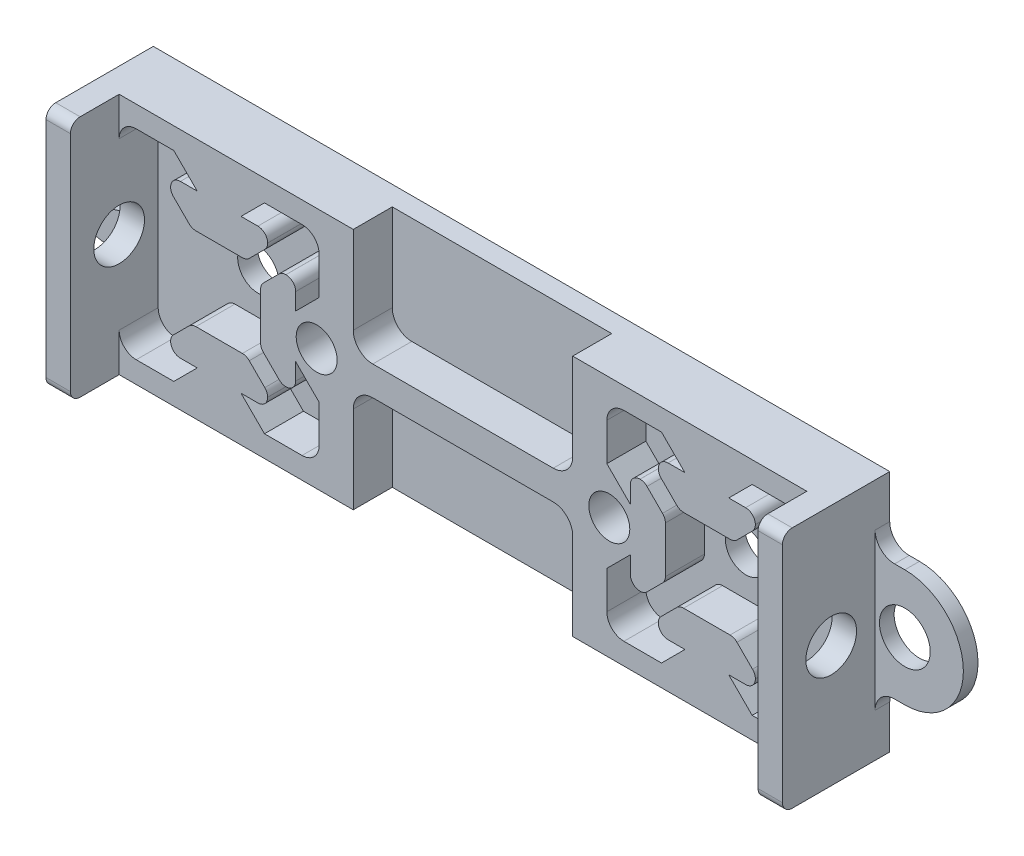
SolidWorks part; units mm, degrees
ref_plane "Front Plane" through (0, 0, 0) normal (0, 0, 1) x (1, 0, 0)
ref_plane "Top Plane" through (0, 0, 0) normal (0, 1, 0) x (1, 0, 0)
ref_plane "Right Plane" through (0, 0, 0) normal (1, 0, 0) x (0, 0, -1)
sketch "Sketch1" plane through (0, 0, 0) normal (0, 0, 1) x (1, 0, 0)
  line L0 (15.6876, 55.3211) -> (115.0437, 55.3211) construction
  line L1 (8.1, 5.225) -> (8.1, 2.85)
  line L2 (-8.5, 10) -> (-4.75, 10)
  line L3 (-10, 8.5) -> (-10, 4.75)
  line L4 (-8.5, -10) -> (-4.75, -10)
  line L5 (10, 8.5) -> (10, 4.75)
  line L6 (6.325, 5.225) -> (4, 2.9)
  line L7 (-8.1, -2.85) -> (-8.1, -5.225)
  line L8 (-2.9, 4) -> (2.9, 4)
  line L9 (-4, 2.9) -> (-4, -2.9)
  line L10 (-2.9, -4) -> (2.9, -4)
  line L11 (4, 2.9) -> (4, -2.9)
  line L12 (2.85, -8.1) -> (5.225, -8.1)
  line L13 (-5.225, -8.1) -> (-2.85, -8.1)
  line L14 (5.225, 6.325) -> (2.9, 4)
  line L15 (-6.4286, 4.975) -> (-4.25, 2.7964)
  line L16 (-4.25, 2.7964) -> (-4.25, -2.7964)
  line L17 (-10, 4.75) -> (-8.1, 2.85)
  line L18 (-4.25, -2.7964) -> (-6.4286, -4.975)
  line L19 (-7.85, -4.975) -> (-6.4286, -4.975)
  line L20 (4.75, -10) -> (8.5, -10)
  line L21 (-7.85, -2.2464) -> (-7.85, -4.975)
  line L22 (-10, -4.75) -> (-10, -8.5)
  line L23 (10, -4.75) -> (10, -8.5)
  line L24 (-10, -4.75) -> (-8.1, -2.85)
  line L25 (-4.75, -10) -> (-2.85, -8.1)
  line L26 (4.75, -10) -> (2.85, -8.1)
  line L27 (10, -4.75) -> (8.1, -2.85)
  line L28 (10, 4.75) -> (8.1, 2.85)
  line L29 (-4.75, 10) -> (-2.85, 8.1)
  line L30 (4.75, 10) -> (2.85, 8.1)
  line L31 (8.1, -2.85) -> (8.1, -5.225)
  line L32 (6.325, -5.225) -> (8.1, -5.225)
  line L33 (5.225, -6.325) -> (5.225, -8.1)
  line L34 (4.75, 10) -> (8.5, 10)
  line L35 (2.85, 8.1) -> (5.225, 8.1)
  line L36 (10, -10) -> (10.975, -10.975) construction
  line L37 (-5.225, 8.1) -> (-2.85, 8.1)
  line L38 (-8.1, -5.225) -> (-6.325, -5.225)
  line L39 (-5.225, 6.325) -> (-2.9, 4)
  line L40 (-8.1, 5.225) -> (-8.1, 2.85)
  line L41 (-5.225, -6.325) -> (-5.225, -8.1)
  line L42 (-6.325, 5.225) -> (-4, 2.9)
  line L43 (-10.25, -4.6464) -> (-7.85, -2.2464)
  line L44 (-10.25, -4.6464) -> (-10.25, -8.5)
  line L45 (-8.5, -10.25) -> (-4.6464, -10.25)
  line L46 (-8.1, 5.225) -> (-6.325, 5.225)
  line L47 (-5.225, 8.1) -> (-5.225, 6.325)
  line L48 (-4.6464, -10.25) -> (-2.2464, -7.85)
  line L49 (-4.975, -7.85) -> (-2.2464, -7.85)
  line L50 (-4.975, -6.4286) -> (-4.975, -7.85)
  line L51 (-2.7964, -4.25) -> (-4.975, -6.4286)
  line L52 (8.1, 5.225) -> (6.325, 5.225)
  line L53 (5.225, 8.1) -> (5.225, 6.325)
  line L54 (-2.7964, -4.25) -> (2.7964, -4.25)
  line L55 (2.7964, -4.25) -> (4.975, -6.4286)
  line L56 (4.975, -6.4286) -> (4.975, -7.85)
  line L57 (2.2464, -7.85) -> (4.975, -7.85)
  line L58 (4.6464, -10.25) -> (2.2464, -7.85)
  line L59 (4.6464, -10.25) -> (8.5, -10.25)
  line L60 (10.25, -4.6464) -> (10.25, -8.5)
  line L61 (10.25, -4.6464) -> (7.85, -2.2464)
  line L62 (7.85, -2.2464) -> (7.85, -4.975)
  line L63 (4, -2.9) -> (6.325, -5.225)
  line L64 (6.4286, -4.975) -> (7.85, -4.975)
  line L65 (4.25, -2.7964) -> (6.4286, -4.975)
  line L66 (2.9, -4) -> (5.225, -6.325)
  line L67 (-2.9, -4) -> (-5.225, -6.325)
  line L68 (4.25, 2.7964) -> (4.25, -2.7964)
  line L69 (6.4286, 4.975) -> (4.25, 2.7964)
  line L70 (-4, -2.9) -> (-6.325, -5.225)
  line L71 (7.85, 4.975) -> (6.4286, 4.975)
  line L72 (7.85, 4.975) -> (7.85, 2.2464)
  line L73 (10.25, 4.6464) -> (7.85, 2.2464)
  line L74 (10.25, 8.5) -> (10.25, 4.6464)
  line L75 (4.6464, 10.25) -> (8.5, 10.25)
  line L76 (4.6464, 10.25) -> (2.2464, 7.85)
  line L77 (2.2464, 7.85) -> (4.975, 7.85)
  line L78 (4.975, 7.85) -> (4.975, 6.4286)
  line L79 (4.975, 6.4286) -> (2.7964, 4.25)
  line L80 (-2.7964, 4.25) -> (2.7964, 4.25)
  line L81 (-4.975, 6.4286) -> (-2.7964, 4.25)
  line L82 (-4.975, 7.85) -> (-4.975, 6.4286)
  line L83 (-4.975, 7.85) -> (-2.2464, 7.85)
  line L84 (-4.6464, 10.25) -> (-2.2464, 7.85)
  line L85 (-8.5, 10.25) -> (-4.6464, 10.25)
  line L86 (-10.25, 8.5) -> (-10.25, 4.6464)
  line L87 (-10.25, 4.6464) -> (-7.85, 2.2464)
  line L88 (-7.85, 4.975) -> (-7.85, 2.2464)
  line L89 (-7.85, 4.975) -> (-6.4286, 4.975)
  line L90 (0, 0) -> (74.0125, 0.5542) construction
  line L91 (25, 17.7637) -> (25, -17.7695) construction
  line L92 (40, -10) -> (39.025, -10.975) construction
  line L93 (57.85, 4.975) -> (56.4286, 4.975)
  line L94 (57.85, 4.975) -> (57.85, 2.2464)
  line L95 (60.25, 4.6464) -> (57.85, 2.2464)
  line L96 (60.25, 8.5) -> (60.25, 4.6464)
  line L97 (54.6464, 10.25) -> (52.2464, 7.85)
  line L98 (54.975, 7.85) -> (52.2464, 7.85)
  line L99 (54.975, 7.85) -> (54.975, 6.4286)
  line L100 (54.975, 6.4286) -> (52.7964, 4.25)
  line L101 (52.7964, 4.25) -> (47.2036, 4.25)
  line L102 (45.025, 6.4286) -> (47.2036, 4.25)
  line L103 (45.025, 7.85) -> (45.025, 6.4286)
  line L104 (47.7536, 7.85) -> (45.025, 7.85)
  line L105 (45.3536, 10.25) -> (47.7536, 7.85)
  line L106 (45.3536, 10.25) -> (41.5, 10.25)
  line L107 (39.75, 8.5) -> (39.75, 4.6464)
  line L108 (39.75, 4.6464) -> (42.15, 2.2464)
  line L109 (42.15, 4.975) -> (42.15, 2.2464)
  line L110 (42.15, 4.975) -> (43.5714, 4.975)
  line L111 (54, -2.9) -> (56.325, -5.225)
  line L112 (43.5714, 4.975) -> (45.75, 2.7964)
  line L113 (45.75, 2.7964) -> (45.75, -2.7964)
  line L114 (52.9, -4) -> (55.225, -6.325)
  line L115 (47.1, -4) -> (44.775, -6.325)
  line L116 (45.75, -2.7964) -> (43.5714, -4.975)
  line L117 (43.5714, -4.975) -> (42.15, -4.975)
  line L118 (46, -2.9) -> (43.675, -5.225)
  line L119 (42.15, -2.2464) -> (42.15, -4.975)
  line L120 (39.75, -4.6464) -> (42.15, -2.2464)
  line L121 (39.75, -4.6464) -> (39.75, -8.5)
  line L122 (45.3536, -10.25) -> (41.5, -10.25)
  line L123 (45.3536, -10.25) -> (47.7536, -7.85)
  line L124 (47.7536, -7.85) -> (45.025, -7.85)
  line L125 (45.025, -6.4286) -> (45.025, -7.85)
  line L126 (47.2036, -4.25) -> (45.025, -6.4286)
  line L127 (52.7964, -4.25) -> (47.2036, -4.25)
  line L128 (44.775, 8.1) -> (44.775, 6.325)
  line L129 (41.9, 5.225) -> (43.675, 5.225)
  line L130 (52.7964, -4.25) -> (54.975, -6.4286)
  line L131 (54.975, -6.4286) -> (54.975, -7.85)
  line L132 (54.975, -7.85) -> (52.2464, -7.85)
  line L133 (54.6464, -10.25) -> (52.2464, -7.85)
  line L134 (55.225, 8.1) -> (55.225, 6.325)
  line L135 (58.1, 5.225) -> (56.325, 5.225)
  line L136 (58.5, -10.25) -> (54.6464, -10.25)
  line L137 (60.25, -4.6464) -> (60.25, -8.5)
  line L138 (60.25, -4.6464) -> (57.85, -2.2464)
  line L139 (56.325, 5.225) -> (54, 2.9)
  line L140 (55.225, -6.325) -> (55.225, -8.1)
  line L141 (58.1, 5.225) -> (58.1, 2.85)
  line L142 (55.225, 6.325) -> (52.9, 4)
  line L143 (58.1, -5.225) -> (56.325, -5.225)
  line L144 (55.225, 8.1) -> (52.85, 8.1)
  line L145 (47.15, 8.1) -> (44.775, 8.1)
  line L146 (45.25, 10) -> (41.5, 10)
  line L147 (44.775, -6.325) -> (44.775, -8.1)
  line L148 (43.675, -5.225) -> (41.9, -5.225)
  line L149 (41.9, -2.85) -> (41.9, -5.225)
  line L150 (45.25, 10) -> (47.15, 8.1)
  line L151 (54.75, 10) -> (52.85, 8.1)
  line L152 (40, 4.75) -> (41.9, 2.85)
  line L153 (40, -4.75) -> (41.9, -2.85)
  line L154 (45.25, -10) -> (47.15, -8.1)
  line L155 (54.75, -10) -> (52.85, -8.1)
  line L156 (60, -4.75) -> (58.1, -2.85)
  line L157 (40, -4.75) -> (40, -8.5)
  line L158 (60, -4.75) -> (60, -8.5)
  line L159 (57.85, -2.2464) -> (57.85, -4.975)
  line L160 (45.25, -10) -> (41.5, -10)
  line L161 (57.85, -4.975) -> (56.4286, -4.975)
  line L162 (54.25, -2.7964) -> (56.4286, -4.975)
  line L163 (60, 4.75) -> (58.1, 2.85)
  line L164 (54.25, 2.7964) -> (54.25, -2.7964)
  line L165 (56.4286, 4.975) -> (54.25, 2.7964)
  line L166 (44.775, 6.325) -> (47.1, 4)
  line L167 (55.225, -8.1) -> (52.85, -8.1)
  line L168 (47.15, -8.1) -> (44.775, -8.1)
  line L169 (46, 2.9) -> (46, -2.9)
  line L170 (52.9, -4) -> (47.1, -4)
  line L171 (54, 2.9) -> (54, -2.9)
  line L172 (52.9, 4) -> (47.1, 4)
  line L173 (58.1, -2.85) -> (58.1, -5.225)
  line L174 (43.675, 5.225) -> (46, 2.9)
  line L175 (40, 8.5) -> (40, 4.75)
  line L176 (58.5, -10) -> (54.75, -10)
  line L177 (60, 8.5) -> (60, 4.75)
  line L178 (58.5, 10) -> (54.75, 10)
  line L179 (41.9, 5.225) -> (41.9, 2.85)
  line L180 (58.5, 10.25) -> (54.6464, 10.25)
  line L182 (-12.75, -12.4529) -> (62.75, -12.4529)
  line L183 (-12.75, -12.4529) -> (-12.75, 12.4471)
  line L184 (-12.75, 12.4471) -> (62.75, 12.4471)
  line L185 (62.75, -12.4529) -> (62.75, 12.4471)
  line L186 (-12.75, -12.4529) -> (62.75, 12.4471) construction
  line L187 (-12.75, 12.4471) -> (62.75, -12.4529) construction
  arc A0 (-8.5, -10) -> (-10, -8.5) centre (-8.5, -8.5) cw
  arc A1 (8.5, -10) -> (10, -8.5) centre (8.5, -8.5) ccw
  arc A2 (10, 8.5) -> (8.5, 10) centre (8.5, 8.5) ccw
  arc A3 (-8.5, 10) -> (-10, 8.5) centre (-8.5, 8.5) ccw
  circle A4 centre (0, 0) radius 2.125
  arc A5 (-8.5, -10.25) -> (-10.25, -8.5) centre (-8.5, -8.5) cw
  arc A6 (8.5, -10.25) -> (10.25, -8.5) centre (8.5, -8.5) ccw
  arc A7 (10.25, 8.5) -> (8.5, 10.25) centre (8.5, 8.5) ccw
  arc A8 (-8.5, 10.25) -> (-10.25, 8.5) centre (-8.5, 8.5) ccw
  arc A9 (58.5, 10.25) -> (60.25, 8.5) centre (58.5, 8.5) cw
  arc A10 (39.75, 8.5) -> (41.5, 10.25) centre (41.5, 8.5) cw
  arc A11 (41.5, -10.25) -> (39.75, -8.5) centre (41.5, -8.5) cw
  arc A12 (58.5, -10.25) -> (60.25, -8.5) centre (58.5, -8.5) ccw
  circle A13 centre (50, 0) radius 2.125
  arc A14 (58.5, 10) -> (60, 8.5) centre (58.5, 8.5) cw
  arc A15 (40, 8.5) -> (41.5, 10) centre (41.5, 8.5) cw
  arc A16 (41.5, -10) -> (40, -8.5) centre (41.5, -8.5) cw
  arc A17 (58.5, -10) -> (60, -8.5) centre (58.5, -8.5) ccw
  point P2 (0, 0)
  point P8 (0, 0)
  point P14 (-10, -10)
  point P20 (0, 0)
  point P49 (10, 10)
  point P52 (-10, 10)
  point P120 (-10, -6.625)
  point P124 (25, -0.0029)
  point P189 (60, 10)
  point P214 (40, 10)
  point P231 (60, -10)
  dimension "D3" = 1.5
  dimension "D4" = 4.25
  dimension "D1" = 20
  dimension "D2" = 20
  dimension "D5" = 0.25
  dimension "D6" = 70
  dimension "D7" = 2.1971
  dimension "D8" = 75.5
  dimension "D9" = 24.9
  dimension "D13" = 5.25
  dimension "D14" = 5.25
  dimension "D15" = 90
  dimension "D16" = 5.25
  dimension "D17" = 5.25
  dimension "D18" = 5.25
  dimension "D19" = 5.25
  dimension "D20" = 5.25
  dimension "D21" = 5.25
  dimension "D22" = 90
  dimension "D23" = 90
  dimension "D24" = 90
  dimension "D25" = 2.85
  dimension "D26" = 2.85
  dimension "D27" = 2.85
  dimension "D28" = 2.85
extrude "Boss-Extrude1" add sketch "Sketch1" along normal blind 4 contours L182 L185 L184 L183 A12 L136 L133 L132 L131 L130 L127 L126 L125 L124 L123 L122 A11 L121 L120 L119 L117 L116 L113 L112 L110 L109 L108 L107 A10 L106 L105 L104 L103 L102 L101 L100 L99 L98 L97 L180 A9 L96 L95 L94 L93 L165 L164 L162 L161 L159
sketch "Sketch2" plane through (0, 0, 0) normal (0, 0, -1) x (-1, 0, 0)
  line L1 (-62.75, 12.4471) -> (12.75, 12.4471)
  line L2 (-62.75, 12.4471) -> (-62.75, -12.4529)
  line L3 (-62.75, -12.4529) -> (12.75, -12.4529)
  line L4 (12.75, 12.4471) -> (12.75, -12.4529)
extrude "Boss-Extrude2" add sketch "Sketch2" along normal blind 2
sketch "Sketch3" plane through (0, 0, 4) normal (0, 0, 1) x (1, 0, 0)
  line L0 (25, 12.4471) -> (25, -12.4529) construction
  line L1 (-12.75, 12.4471) -> (62.75, 12.4471) construction
  line L2 (-12.75, -12.4529) -> (62.75, -12.4529) construction
  line L4 (13.75, -12.4529) -> (36.25, -12.4529)
  line L5 (13.75, -12.4529) -> (13.75, 12.4471)
  line L6 (13.75, 12.4471) -> (36.25, 12.4471)
  line L7 (36.25, -12.4529) -> (36.25, 12.4471)
  line L8 (13.75, -12.4529) -> (36.25, 12.4471) construction
  line L9 (13.75, 12.4471) -> (36.25, -12.4529) construction
  point P6 (25, -0.0029)
  dimension "D1" = 22.5
extrude "Cut-Extrude1" cut sketch "Sketch3" against normal blind 4
fillet "Fillet1" radius 1 48 edges at (-4.25, -2.7964, 2) (-6.4286, -4.975, 2) (-7.85, -4.975, 2) (-4.975, -7.85, 2) (-4.975, -6.4286, 2) (-2.7964, -4.25, 2) (2.7964, -4.25, 2) (4.975, -6.4286, 2) (4.975, -7.85, 2) (7.85, -4.975, 2) (6.4286, -4.975, 2) (4.25, -2.7964, 2) (4.25, 2.7964, 2) (6.4286, 4.975, 2) (7.85, 4.975, 2) (4.975, 7.85, 2) (4.975, 6.4286, 2) (2.7964, 4.25, 2) (-4.25, 2.7964, 2) (-2.7964, 4.25, 2) (-6.4286, 4.975, 2) (-7.85, 4.975, 2) (-4.975, 6.4286, 2) (-4.975, 7.85, 2) (45.025, -7.85, 2) (42.15, -4.975, 2) (43.5714, -4.975, 2) (45.025, -6.4286, 2) (47.2036, -4.25, 2) (45.75, -2.7964, 2) (52.7964, -4.25, 2) (54.975, -6.4286, 2) (54.975, -7.85, 2) (54.25, -2.7964, 2) (56.4286, -4.975, 2) (57.85, -4.975, 2) (54.25, 2.7964, 2) (56.4286, 4.975, 2) (57.85, 4.975, 2) (45.75, 2.7964, 2) (43.5714, 4.975, 2) (42.15, 4.975, 2) (54.975, 6.4286, 2) (54.975, 7.85, 2) (52.7964, 4.25, 2) (47.2036, 4.25, 2) (45.025, 6.4286, 2) (45.025, 7.85, 2)
sketch "Sketch4" plane through (0, 0, 0) normal (0, 0, 1) x (1, 0, 0)
  line L0 (25, 12.4471) -> (25, -12.4529) construction
  line L1 (36.25, 12.4471) -> (13.75, 12.4471) construction
  line L2 (13.75, -12.4529) -> (36.25, -12.4529) construction
  circle A0 centre (0, 0) radius 2.1
  circle A1 centre (50, 0) radius 2.1
  dimension "D1" = 4.2
extrude "Cut-Extrude2" cut sketch "Sketch4" against normal through all
sketch "Sketch5" plane through (0, 0, 4) normal (0, 0, 1) x (1, 0, 0)
  line L0 (-12.75, -12.4529) -> (13.75, -12.4529) construction
  line L1 (-12.75, 12.4471) -> (-10.25, 12.4471)
  line L2 (-12.75, 12.4471) -> (-12.75, -12.4529)
  line L3 (-12.75, -12.4529) -> (-10.25, -12.4529)
  line L4 (-10.25, 12.4471) -> (-10.25, -12.4529)
  line L5 (36.25, -12.4529) -> (62.75, -12.4529) construction
  line L6 (62.75, 12.4471) -> (60.25, 12.4471)
  line L7 (62.75, 12.4471) -> (62.75, -12.4529)
  line L8 (62.75, -12.4529) -> (60.25, -12.4529)
  line L9 (60.25, 12.4471) -> (60.25, -12.4529)
  dimension "D1" = 2.5
  dimension "D2" = 2.5
extrude "Boss-Extrude3" add sketch "Sketch5" along normal blind 5
sketch "Sketch7" plane through (0, 0, 4) normal (0, 0, 1) x (1, 0, 0)
  line L5 (-7.85, 2.2464) -> (-10.25, 4.6464)
  line L6 (-7.85, 2.2464) -> (-10.25, 4.6464)
  line L7 (-10.25, 4.6464) -> (-10.25, -4.6464)
  line L8 (-10.25, 4.6464) -> (-10.25, -4.6464)
  line L9 (-10.25, -4.6464) -> (-7.85, -2.2464)
  line L10 (-10.25, -4.6464) -> (-7.85, -2.2464)
  line L11 (-7.85, -2.2464) -> (-7.85, -3.975)
  line L18 (-7.85, -2.2464) -> (-7.85, -3.975)
  line L19 (-6.85, -4.975) -> (-6.8428, -4.975)
  line L20 (-6.85, -4.975) -> (-6.8428, -4.975)
  line L21 (-6.1357, -4.6821) -> (-4.5429, -3.0893)
  line L22 (-6.1357, -4.6821) -> (-4.5429, -3.0893)
  line L23 (-4.25, -2.3822) -> (-4.25, 2.3822)
  line L24 (-4.25, -2.3822) -> (-4.25, 2.3822)
  line L25 (-4.5429, 3.0893) -> (-6.1357, 4.6821)
  line L26 (-4.5429, 3.0893) -> (-6.1357, 4.6821)
  line L27 (-6.8428, 4.975) -> (-6.85, 4.975)
  line L28 (-6.8428, 4.975) -> (-6.85, 4.975)
  line L29 (-7.85, 3.975) -> (-7.85, 2.2464)
  line L30 (-7.85, 3.975) -> (-7.85, 2.2464)
  line L41 (57.85, -2.2464) -> (60.25, -4.6464)
  line L42 (60.25, -4.6464) -> (60.25, 4.6464)
  line L43 (60.25, 4.6464) -> (57.85, 2.2464)
  line L44 (57.85, 2.2464) -> (57.85, 3.975)
  line L45 (56.85, 4.975) -> (56.8428, 4.975)
  line L46 (56.1357, 4.6821) -> (54.5429, 3.0893)
  line L47 (54.25, 2.3822) -> (54.25, -2.3822)
  line L48 (54.5429, -3.0893) -> (56.1357, -4.6821)
  line L49 (56.8428, -4.975) -> (56.85, -4.975)
  line L50 (57.85, -3.975) -> (57.85, -2.2464)
  line L51 (57.85, -2.2464) -> (60.25, -4.6464)
  line L52 (60.25, -4.6464) -> (60.25, 4.6464)
  line L53 (60.25, 4.6464) -> (57.85, 2.2464)
  line L54 (57.85, 2.2464) -> (57.85, 3.975)
  line L55 (56.85, 4.975) -> (56.8428, 4.975)
  line L56 (56.1357, 4.6821) -> (54.5429, 3.0893)
  line L57 (54.25, 2.3822) -> (54.25, -2.3822)
  line L58 (54.5429, -3.0893) -> (56.1357, -4.6821)
  line L59 (56.8428, -4.975) -> (56.85, -4.975)
  line L60 (57.85, -3.975) -> (57.85, -2.2464)
  arc A6 (-7.85, -3.975) -> (-6.85, -4.975) centre (-6.85, -3.975) ccw
  arc A7 (-7.85, -3.975) -> (-6.85, -4.975) centre (-6.85, -3.975) ccw
  arc A8 (-6.8428, -4.975) -> (-6.1357, -4.6821) centre (-6.8428, -3.975) ccw
  arc A9 (-6.8428, -4.975) -> (-6.1357, -4.6821) centre (-6.8428, -3.975) ccw
  arc A10 (-4.5429, -3.0893) -> (-4.25, -2.3822) centre (-5.25, -2.3822) ccw
  arc A11 (-4.5429, -3.0893) -> (-4.25, -2.3822) centre (-5.25, -2.3822) ccw
  arc A12 (-4.25, 2.3822) -> (-4.5429, 3.0893) centre (-5.25, 2.3822) ccw
  arc A13 (-4.25, 2.3822) -> (-4.5429, 3.0893) centre (-5.25, 2.3822) ccw
  arc A14 (-6.1357, 4.6821) -> (-6.8428, 4.975) centre (-6.8428, 3.975) ccw
  arc A15 (-6.1357, 4.6821) -> (-6.8428, 4.975) centre (-6.8428, 3.975) ccw
  arc A16 (-6.85, 4.975) -> (-7.85, 3.975) centre (-6.85, 3.975) ccw
  arc A17 (-6.85, 4.975) -> (-7.85, 3.975) centre (-6.85, 3.975) ccw
  arc A24 (57.85, 3.975) -> (56.85, 4.975) centre (56.85, 3.975) ccw
  arc A25 (56.8428, 4.975) -> (56.1357, 4.6821) centre (56.8428, 3.975) ccw
  arc A26 (54.5429, 3.0893) -> (54.25, 2.3822) centre (55.25, 2.3822) ccw
  arc A27 (54.25, -2.3822) -> (54.5429, -3.0893) centre (55.25, -2.3822) ccw
  arc A28 (56.1357, -4.6821) -> (56.8428, -4.975) centre (56.8428, -3.975) ccw
  arc A29 (56.85, -4.975) -> (57.85, -3.975) centre (56.85, -3.975) ccw
  arc A30 (57.85, 3.975) -> (56.85, 4.975) centre (56.85, 3.975) ccw
  arc A31 (56.8428, 4.975) -> (56.1357, 4.6821) centre (56.8428, 3.975) ccw
  arc A32 (54.5429, 3.0893) -> (54.25, 2.3822) centre (55.25, 2.3822) ccw
  arc A33 (54.25, -2.3822) -> (54.5429, -3.0893) centre (55.25, -2.3822) ccw
  arc A34 (56.1357, -4.6821) -> (56.8428, -4.975) centre (56.8428, -3.975) ccw
  arc A35 (56.85, -4.975) -> (57.85, -3.975) centre (56.85, -3.975) ccw
  dimension "D2" = 0
  dimension "D1" = 0
sketch "Sketch8" plane through (62.75, 0, 0) normal (1, 0, 0) x (0, 0, -1)
  line L0 (-9, -0.0029) -> (2, -0.0029) construction
  line L1 (-9, -12.4529) -> (-9, 12.4471) construction
  line L2 (2, 12.4471) -> (2, -12.4529) construction
  circle A0 centre (-4, -0.0029) radius 2.6
  dimension "D1" = 5
  dimension "D2" = 5.2
extrude "Cut-Extrude4" cut sketch "Sketch8" against normal blind 2.5
sketch "Sketch9" plane through (-12.75, 0, 0) normal (-1, 0, 0) x (0, 0, 1)
  line L0 (9, 0) -> (-2, 0) construction
  line L1 (9, 12.4471) -> (9, -12.4529) construction
  line L2 (-2, -12.4529) -> (-2, 12.4471) construction
  circle A0 centre (4, 0) radius 2.6
  dimension "D1" = 5.2
  dimension "D2" = 5
extrude "Cut-Extrude5" cut sketch "Sketch9" against normal blind 2.5
sketch "Sketch10" plane through (0, 0, -2) normal (0, 0, -1) x (-1, 0, 0)
  line L0 (-25, -12.4529) -> (-25, 12.4471) construction
  line L1 (-62.75, -12.4529) -> (12.75, -12.4529) construction
  line L2 (12.75, 12.4471) -> (-62.75, 12.4471) construction
  line L3 (0, 0) -> (-50, 0) construction
  circle A0 centre (-10, 0) radius 2.1
  circle A1 centre (-40, 0) radius 2.1
  dimension "D1" = 30
  dimension "D2" = 4.2
extrude "Cut-Extrude6" cut sketch "Sketch10" against normal through all
extrude "Cut-Extrude7" cut sketch "Sketch7" against normal blind 4
sketch "Sketch11" plane through (0, 0, 0) normal (0, 0, 1) x (1, 0, 0)
  line L0 (36.25, -0.0029) -> (13.75, -0.0029) construction
  line L1 (36.25, -12.4529) -> (36.25, 12.4471) construction
  line L2 (13.75, 12.4471) -> (13.75, -12.4529) construction
  line L4 (36.25, 1.4971) -> (13.75, 1.4971)
  line L5 (36.25, 1.4971) -> (36.25, -1.5029)
  line L6 (36.25, -1.5029) -> (13.75, -1.5029)
  line L7 (13.75, 1.4971) -> (13.75, -1.5029)
  line L8 (36.25, 1.4971) -> (13.75, -1.5029) construction
  line L9 (36.25, -1.5029) -> (13.75, 1.4971) construction
  point P6 (25, -0.0029)
  dimension "D1" = 3
extrude "Boss-Extrude4" add sketch "Sketch11" along normal up to surface (4 mm away) up to face at (42.1, 0, 4)
fillet "Fillet2" radius 2 4 edges at (13.75, -1.5029, 2) (13.75, 1.4971, 2) (36.25, 1.4971, 2) (36.25, -1.5029, 2)
fillet "Fillet3" radius 1 4 edges at (-11.5, 12.4471, 9) (-11.5, -12.4529, 9) (61.5, 12.4471, 9) (61.5, -12.4529, 9)
sketch "Sketch12" plane through (0, 0, -2) normal (0, 0, -1) x (-1, 0, 0)
  line L0 (25.9887, 0) -> (-76.4862, 0) construction
  line L1 (-25, -12.4529) -> (-25, 12.4471) construction
  line L2 (-62.75, -12.4529) -> (12.75, -12.4529) construction
  line L3 (12.75, 12.4471) -> (-62.75, 12.4471) construction
  line L4 (15.8, -6) -> (12.75, -6)
  line L5 (12.75, -12.4529) -> (12.75, 12.4471) construction
  line L6 (12.75, -6) -> (12.75, 6)
  line L7 (12.75, 6) -> (15.8, 6)
  line L8 (-62.75, -6) -> (-62.75, 6)
  line L9 (-65.8, -6) -> (-62.75, -6)
  line L10 (-62.75, 6) -> (-65.8, 6)
  circle A0 centre (15.8, 0) radius 2.6
  circle A1 centre (15.8, 0) radius 6
  circle A2 centre (-65.8, 0) radius 2.6
  circle A3 centre (-65.8, 0) radius 6
  line M8 (-62.75, 12.4471) -> (-62.75, -12.4529)
  line M10 (12.75, -12.4529) -> (12.75, 12.4471)
  dimension "D1" = 5.2
  dimension "D2" = 81.6
  dimension "D3" = 12
extrude "Boss-Extrude5" add sketch "Sketch12" against normal blind 1.5 contours A1 L6 A0 | A1 L4 M10 | A1 L7 M10 | A3 L9 M8 | A3 L8 A2 | L10 A3 M8
fillet "Fillet4" radius 2 4 edges at (62.75, -6, -1.25) (62.75, 6, -1.25) (-12.75, 6, -1.25) (-12.75, -6, -1.25)
